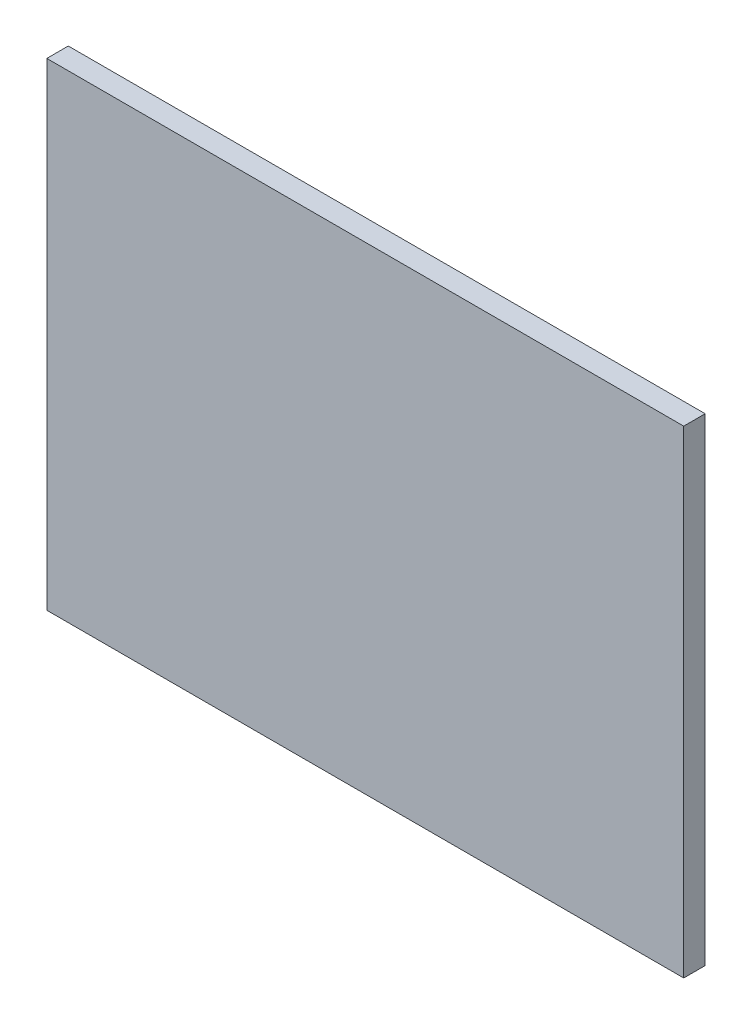
SolidWorks part; units mm, degrees
ref_plane "Front Plane" through (0, 0, 0) normal (0, 0, 1) x (1, 0, 0)
ref_plane "Top Plane" through (0, 0, 0) normal (0, 1, 0) x (1, 0, 0)
ref_plane "Right Plane" through (0, 0, 0) normal (1, 0, 0) x (0, 0, -1)
sketch "Sketch1" plane through (0, 0, 0) normal (0, 0, 1) x (1, 0, 0)
  line L0 (213.3333, 480) -> (1066.6667, 480) construction
sketch "Sketch2" plane through (0, 0, 0) normal (0, 0, 1) x (1, 0, 0)
  line L0 (213.3333, 480.748) -> (1066.6667, 480.748) construction
sketch "Sketch3" plane through (0, 0, 0) normal (0, 0, 1) x (1, 0, 0)
  line L1 (0, 222.5249) -> (296.5506, 222.5249)
  line L2 (0, 222.5249) -> (0, 0)
  line L3 (0, 0) -> (296.5506, 0)
  line L4 (296.5506, 222.5249) -> (296.5506, 0)
extrude "Boss-Extrude1" add sketch "Sketch3" along normal blind 10
